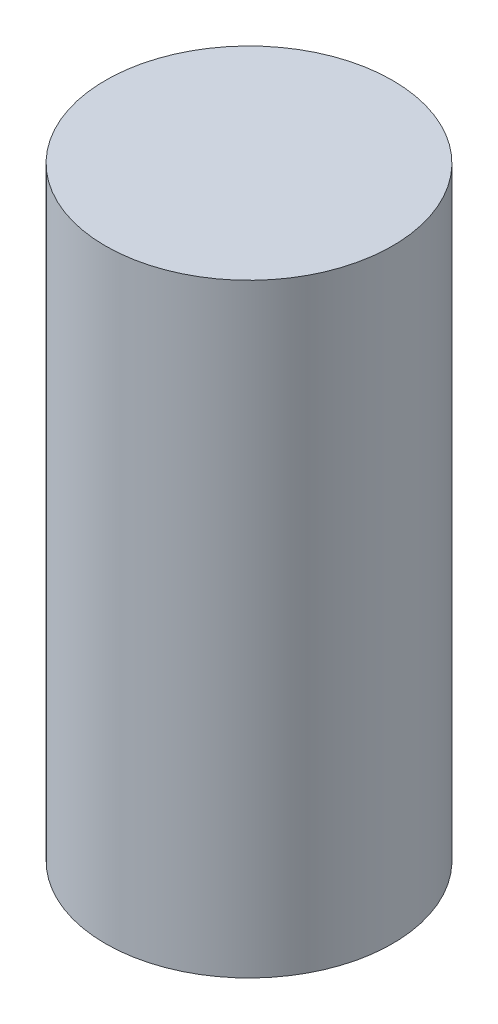
SolidWorks part; units mm, degrees
ref_plane "Front Plane" through (0, 0, 0) normal (0, 0, 1) x (1, 0, 0)
ref_plane "Top Plane" through (0, 0, 0) normal (0, 1, 0) x (1, 0, 0)
ref_plane "Right Plane" through (0, 0, 0) normal (1, 0, 0) x (0, 0, -1)
sketch "Sketch1" plane through (0, 0, 0) normal (0, 1, 0) x (1, 0, 0)
  circle A0 centre (0, 0) radius 95
extrude "Boss-Extrude1" add sketch "Sketch1" along normal blind 400
